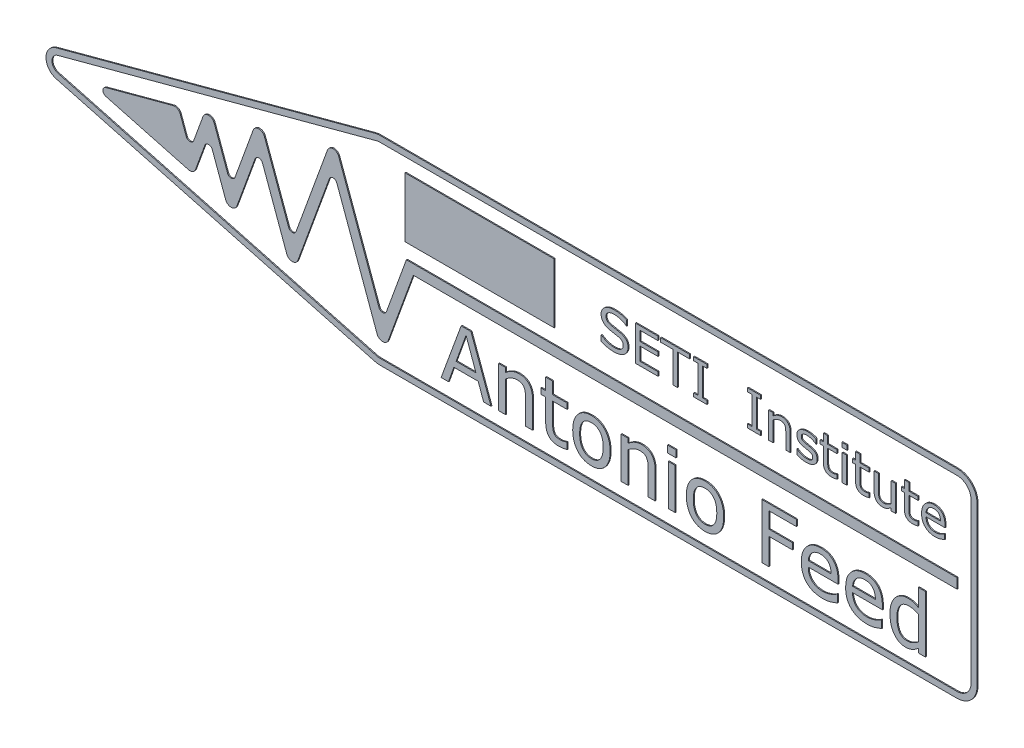
SolidWorks part; units mm, degrees
ref_plane "Front Plane" through (0, 0, 0) normal (0, 0, 1) x (1, 0, 0)
ref_plane "Top Plane" through (0, 0, 0) normal (0, 1, 0) x (1, 0, 0)
ref_plane "Right Plane" through (0, 0, 0) normal (1, 0, 0) x (0, 0, -1)
sketch "Sketch3" plane through (0, 0, 0) normal (0, 0, 1) x (1, 0, 0)
  line L0 (0, -20.32) -> (0, 20.32)
  line L1 (-5.08, 25.4) -> (-152.4, 25.4)
  line L2 (-153.7148, 25.2269) -> (-235.0439, 3.4348)
  line L3 (-235.0439, -3.4348) -> (-153.7148, -25.2269)
  line L4 (-152.4, -25.4) -> (-5.08, -25.4)
  line L5 (-5.08, 23.876) -> (-152.4, 23.876)
  line L6 (-153.3204, 23.7548) -> (-234.6495, 1.9628)
  line L7 (-234.6495, -1.9628) -> (-153.3204, -23.7548)
  line L8 (-152.4, -23.876) -> (-5.08, -23.876)
  line L9 (-1.524, -20.32) -> (-1.524, 20.32)
  arc A0 (0, -20.32) -> (-5.08, -25.4) centre (-5.08, -20.32) cw
  arc A1 (-153.7148, -25.2269) -> (-152.4, -25.4) centre (-152.4, -20.32) ccw
  arc A2 (-152.4, 25.4) -> (-153.7148, 25.2269) centre (-152.4, 20.32) ccw
  arc A3 (0, 20.32) -> (-5.08, 25.4) centre (-5.08, 20.32) ccw
  arc A4 (-235.0439, 3.4348) -> (-235.0439, -3.4348) centre (-234.1236, 0) ccw
  arc A5 (-152.4, 23.876) -> (-153.3204, 23.7548) centre (-152.4, 20.32) ccw
  arc A6 (-234.6495, 1.9628) -> (-234.6495, -1.9628) centre (-234.1236, 0) ccw
  arc A7 (-153.3204, -23.7548) -> (-152.4, -23.876) centre (-152.4, -20.32) ccw
  arc A8 (-1.524, -20.32) -> (-5.08, -23.876) centre (-5.08, -20.32) cw
  arc A9 (-1.524, 20.32) -> (-5.08, 23.876) centre (-5.08, 20.32) ccw
  dimension "D1" = 5.08
  dimension "D2" = 3.556
  dimension "D7" = 237.6796
  dimension "D4" = 15
  dimension "D5" = 50.8
  dimension "D6" = 152.4
  dimension "D3" = 1.524
extrude "Boss-Extrude2" add sketch "Sketch3" along normal blind 0.254
sketch "Sketch1" plane through (0, 0, 0) normal (0, 0, 1) x (1, 0, 0)
  line L0 (-153.3204, 23.7548) -> (-234.6495, 1.9628) construction
  line L1 (-5.08, 1.27) -> (-145.6693, 1.27)
  line L2 (-145.6693, 1.27) -> (-150.7708, -12.7464)
  line L3 (-152.6803, -12.7464) -> (-162.9502, 15.47)
  line L4 (-165.8144, 15.47) -> (-173.835, -6.5664)
  line L5 (-175.7444, -6.5664) -> (-181.9154, 10.3883)
  line L6 (-184.7796, 10.3883) -> (-189.4297, -2.3878)
  line L7 (-191.3392, -2.3878) -> (-194.7387, 6.9523)
  line L8 (-5.08, 1.27) -> (-5.08, -1.27)
  line L9 (-5.08, -1.27) -> (-143.8907, -1.27)
  line L10 (-143.8907, -1.27) -> (-150.2935, -18.8613)
  line L11 (-153.1576, -18.8613) -> (-163.4276, 9.3551)
  line L12 (-165.337, 9.3551) -> (-173.3576, -12.6813)
  line L13 (-176.2218, -12.6813) -> (-182.3928, 4.2733)
  line L14 (-184.3022, 4.2733) -> (-188.9523, -8.5027)
  line L15 (-191.8165, -8.5027) -> (-195.216, 0.8374)
  line L16 (-205.2356, 5.5799) -> (-222.3974, 0.9814)
  line L17 (-222.3974, -0.9814) -> (-201.3232, -6.6282)
  line L19 (-143.8907, -1.27) -> (-145.6693, 1.27) construction
  line L20 (-226.06, 0) -> (-274.8669, 0) construction
  line L21 (-199.4967, -5.6774) -> (-197.1255, 0.8374)
  line L23 (-197.6028, 6.9523) -> (-199.974, 0.4375)
  line L24 (-201.8835, 0.4375) -> (-203.4091, 4.6291)
  line L26 (-220.0164, 4.8477) -> (-129.5878, -19.3825) construction
  line L27 (-218.1704, -4.3531) -> (-130.955, 19.0162) construction
  arc A0 (-150.7708, -12.7464) -> (-152.6803, -12.7464) centre (-151.7255, -12.3989) cw
  arc A1 (-163.4276, 9.3551) -> (-165.337, 9.3551) centre (-164.3823, 9.0076) ccw
  arc A2 (-182.3928, 4.2733) -> (-184.3022, 4.2733) centre (-183.3475, 3.9258) ccw
  arc A3 (-189.4297, -2.3878) -> (-191.3392, -2.3878) centre (-190.3844, -2.0403) cw
  arc A4 (-150.2935, -18.8613) -> (-153.1576, -18.8613) centre (-151.7255, -18.3401) cw
  arc A5 (-162.9502, 15.47) -> (-165.8144, 15.47) centre (-164.3823, 14.9487) ccw
  arc A6 (-173.3576, -12.6813) -> (-176.2218, -12.6813) centre (-174.7897, -12.1601) cw
  arc A7 (-173.835, -6.5664) -> (-175.7444, -6.5664) centre (-174.7897, -6.2189) cw
  arc A8 (-188.9523, -8.5027) -> (-191.8165, -8.5027) centre (-190.3844, -7.9815) cw
  arc A9 (-181.9154, 10.3883) -> (-184.7796, 10.3883) centre (-183.3475, 9.867) ccw
  arc A10 (-222.3974, -0.9814) -> (-222.3974, 0.9814) centre (-222.1345, 0) cw
  arc A11 (-203.4091, 4.6291) -> (-205.2356, 5.5799) centre (-204.8412, 4.1078) ccw
  arc A12 (-201.3232, -6.6282) -> (-199.4967, -5.6774) centre (-200.9287, -5.1561) ccw
  arc A13 (-199.974, 0.4375) -> (-201.8835, 0.4375) centre (-200.9287, 0.785) cw
  arc A14 (-197.1255, 0.8374) -> (-195.216, 0.8374) centre (-196.1708, 0.4899) cw
  arc A15 (-194.7387, 6.9523) -> (-197.6028, 6.9523) centre (-196.1708, 6.431) ccw
  point P41 (-5.08, 0)
  point P43 (-144.78, 0)
  dimension "D13" = 1.524
  dimension "D28" = 1.016
  dimension "D12" = 1.524
  dimension "D6" = 1.016
  dimension "D9" = 1.016
  dimension "D4" = 2.54
  dimension "D5" = 2.54
  dimension "D7" = 110
  dimension "D8" = 110
  dimension "D10" = 4.119
  dimension "D24" = 139.7
  dimension "D26" = 5.08
  dimension "D35" = 15
  dimension "D36" = 81.28
extrude "Boss-Extrude1" add sketch "Sketch1" along normal blind 0.254
sketch "Sketch4" plane through (0, 0, 0) normal (0, 0, 1) x (1, 0, 0)
  line L0 (-210.82, 7.62) -> (-7.62, 7.62) construction
  text T0 "SETI  Institute" font "Verdana" height 8.89
  dimension "D1" = 7.62
  dimension "D2" = 7.62
  dimension "D3" = 203.2
extrude "BE-00 Text SETI Inst" add sketch "Sketch4" along normal blind 0.254 separate body
sketch "Sketch6" plane through (0, 0, 0) normal (0, 0, 1) x (1, 0, 0)
  line L0 (-163.83, -20.32) -> (-11.43, -20.32) construction
  text T0 "Antonio Feed" font "Verdana" height 13.97
  dimension "D1" = 20.32
  dimension "D2" = 11.43
  dimension "D3" = 152.4
extrude "BE-00 Text Franklin" add sketch "Sketch6" along normal blind 0.254 separate body
sketch "Sketch5" plane through (0, 0, 0) normal (0, 0, 1) x (1, 0, 0)
  line L1 (-146.05, 20.32) -> (-107.95, 20.32)
  line L2 (-146.05, 20.32) -> (-146.05, 5.08)
  line L3 (-146.05, 5.08) -> (-107.95, 5.08)
  line L4 (-107.95, 20.32) -> (-107.95, 5.08)
  dimension "D1" = 5.08
  dimension "D2" = 38.1
  dimension "D3" = 15.24
  dimension "D4" = 107.95
extrude "Boss-Extrude4" add sketch "Sketch5" along normal blind 0.254 separate body
